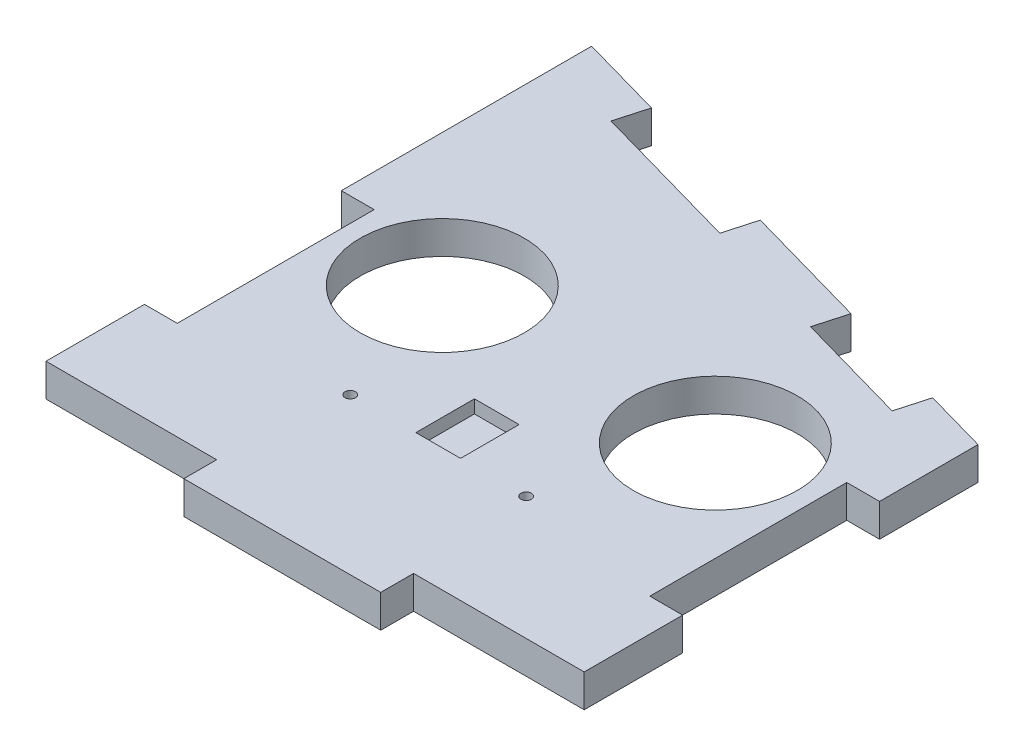
SolidWorks part; units mm, degrees
ref_plane "Front Plane" through (0, 0, 0) normal (0, 0, 1) x (1, 0, 0)
ref_plane "Top Plane" through (0, 0, 0) normal (0, 1, 0) x (1, 0, 0)
ref_plane "Right Plane" through (0, 0, 0) normal (1, 0, 0) x (0, 0, -1)
sketch "Sketch1" plane through (0, 0, 0) normal (0, 1, 0) x (1, 0, 0)
  line L0 (0, 0) -> (16.51, 0)
  line L1 (16.51, 0) -> (16.51, -3.175)
  line L2 (16.51, -3.175) -> (35.56, -3.175)
  line L3 (35.56, -3.175) -> (35.56, 0)
  line L4 (35.56, 0) -> (52.07, 0)
  line L5 (52.07, 0) -> (52.07, 9.525)
  line L6 (52.07, 9.525) -> (48.895, 9.525)
  line L7 (48.895, 9.525) -> (48.895, 28.575)
  line L8 (48.895, 28.575) -> (52.07, 28.575)
  line L9 (52.07, 28.575) -> (52.07, 38.1)
  line L10 (52.07, 38.1) -> (45.9585, 39.824)
  line L11 (0, 52.7881) -> (0, 28.575)
  line L12 (0, 28.575) -> (3.175, 28.575)
  line L13 (3.175, 28.575) -> (3.175, 9.525)
  line L14 (3.175, 9.525) -> (0, 9.525)
  line L15 (0, 9.525) -> (0, 0)
  line L16 (52.07, 38.1) -> (31.283, 38.1) construction
  line L17 (12.827, 25.5124) -> (39.243, 25.5124) construction
  line L18 (26.035, 25.5124) -> (26.035, -3.175) construction
  line L19 (45.9585, 39.824) -> (45.0965, 36.7682)
  line L20 (45.0965, 36.7682) -> (34.0958, 39.8713)
  line L21 (34.0958, 39.8713) -> (34.9578, 42.9271)
  line L22 (34.9578, 42.9271) -> (22.7348, 46.375)
  line L23 (22.7348, 46.375) -> (21.8728, 43.3193)
  line L24 (21.8728, 43.3193) -> (7.2052, 47.4568)
  line L25 (7.2052, 47.4568) -> (8.0672, 50.5125)
  line L26 (8.0672, 50.5125) -> (0, 52.7881)
  line L27 (3.175, 28.575) -> (3.175, 51.8925) construction
  line L28 (3.175, 9.525) -> (3.175, 0) construction
  line L29 (48.895, 28.575) -> (48.895, 38.9956) construction
  line L30 (48.895, 9.525) -> (48.895, 0) construction
  circle A0 centre (12.827, 25.5124) radius 7.9375
  circle A1 centre (39.243, 25.5124) radius 7.9375
  dimension "D1" = 15.875
  dimension "D2" = 45.72
  dimension "D3" = 3.175
  dimension "D4" = 38.1
  dimension "D5" = 3.175
  dimension "D6" = 19.05
  dimension "D7" = 19.05
  dimension "D8" = 26.416
  dimension "D9" = 15.24
  dimension "D10" = 11.43
  dimension "D11" = 8.382
  dimension "D12" = 12.7
  dimension "D13" = 6.35
  dimension "D14" = 54.102
  dimension "D15" = 51.8925
  dimension "D16" = 38.9956
  dimension "D17" = 9.525
  dimension "D18" = 52.7881
extrude "Boss-Extrude1" add sketch "Sketch1" along normal blind 3.175
sketch "Sketch2" plane through (0, 3.175, 0) normal (0, 1, 0) x (1, 0, 0)
  line L0 (39.243, 17.5749) -> (20.6827, 17.5749) construction
  line L1 (23.876, 17.5749) -> (28.194, 17.5749)
  line L2 (23.876, 17.5749) -> (23.876, 11.9107)
  line L3 (23.876, 11.9107) -> (28.194, 11.9107)
  line L4 (28.194, 17.5749) -> (28.194, 11.9107)
  line L5 (26.035, -3.175) -> (26.035, 11.9107) construction
  line L6 (16.51, -3.175) -> (35.56, -3.175) construction
  circle A0 centre (39.243, 25.5124) radius 7.9375 construction
  dimension "D1" = 5.6642
  dimension "D2" = 4.318
extrude "Cut-Extrude1" cut sketch "Sketch2" against normal blind 1.27
sketch "Sketch3" plane through (0, 3.175, 0) normal (0, 1, 0) x (1, 0, 0)
  line L0 (23.876, 11.9107) -> (17.526, 11.9107) construction
  line L1 (28.194, 11.9107) -> (34.544, 11.9107) construction
  circle A0 centre (17.526, 11.9107) radius 0.508
  circle A1 centre (34.544, 11.9107) radius 0.508
  dimension "D1" = 1.016
  dimension "D2" = 6.35
extrude "Cut-Extrude2" cut sketch "Sketch3" against normal through all
